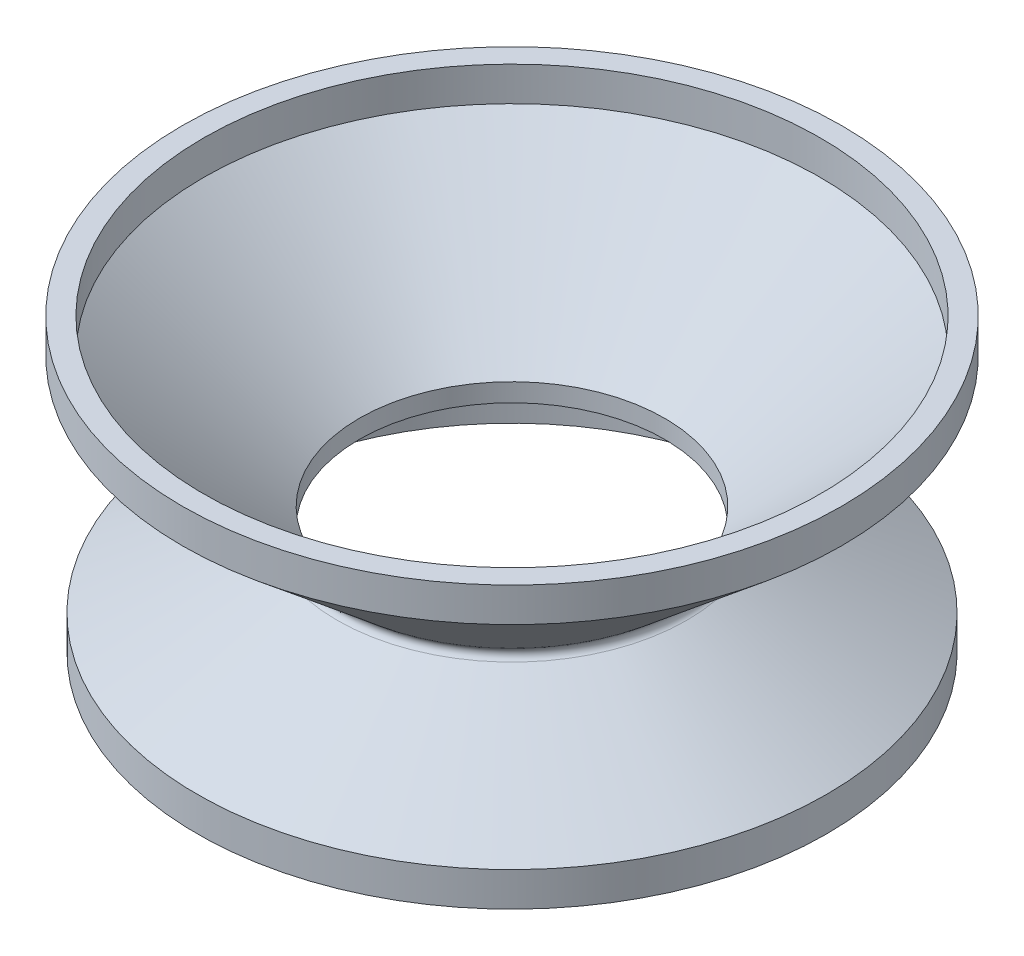
SolidWorks part; units mm, degrees
ref_plane "Front Plane" through (0, 0, 0) normal (0, 0, 1) x (1, 0, 0)
ref_plane "Top Plane" through (0, 0, 0) normal (0, 1, 0) x (1, 0, 0)
ref_plane "Right Plane" through (0, 0, 0) normal (1, 0, 0) x (0, 0, -1)
sketch "Sketch1" plane through (0, 0, 0) normal (0, 0, 1) x (1, 0, 0)
  line L0 (-42.6436, 0) -> (43.9692, 0) construction
  line L1 (0.6628, 0) -> (-8.8712, 8)
  line L2 (0.6628, 0) -> (-7.9975, -5)
  line L3 (1.4628, -0.6928) -> (-5.9975, -5)
  line L5 (-8.8712, 8) -> (-7.6267, 8)
  line L6 (-7.9975, -5) -> (-5.9975, -5)
  line L7 (10.3733, 7.609) -> (10.3733, -7.609) construction
  line L8 (2.3996, -0.152) -> (-16.3835, 15.6089) construction
  line L9 (0.6628, 0) -> (-17.0263, 14.8429) construction
  line L10 (0.6628, 0) -> (-17.9865, -10.7671) construction
  line L11 (2.3996, -0.152) -> (-17.4865, -11.6332) construction
  line L12 (0.6628, 0) -> (2.2628, 0) construction
  line L13 (1.4628, -0.6928) -> (1.4628, 0.373)
  line L14 (1.4628, 0.373) -> (-7.6267, 8)
  point P11 (1.4628, 0)
  dimension "D1" = 40
  dimension "D2" = 30
  dimension "D4" = 8
  dimension "D5" = 5
  dimension "D6" = 18
  dimension "D7" = 1.6
  dimension "D8" = 0.8
  dimension "D3" = 1
revolve "Revolve1" add sketch "Sketch1" angle 360 about L7
scale "Scale1" [suppressed]
fillet "Fillet2" radius 0.4 1 edges at (0.6628, 0, 0)
sketch "Sketch2" plane through (0, 8, 0) normal (0, 1, 0) x (1, 0, 0)
  circle A0 centre (10.3733, 0) radius 19.2446 construction
  circle A1 centre (10.3733, 0) radius 18 construction
  circle A2 centre (10.3733, 0) radius 19.2446
  circle A3 centre (10.3733, 0) radius 18
extrude "Boss-Extrude1" add sketch "Sketch2" along normal blind 2
sketch "Sketch3" plane through (0, -5, 0) normal (0, -1, 0) x (1, 0, 0)
  circle A0 centre (10.3733, 0) radius 16.3708 construction
  circle A1 centre (10.3733, 0) radius 18.3708 construction
  circle A2 centre (10.3733, 0) radius 16.3708
  circle A3 centre (10.3733, 0) radius 18.3708
extrude "Boss-Extrude2" add sketch "Sketch3" along normal blind 2
